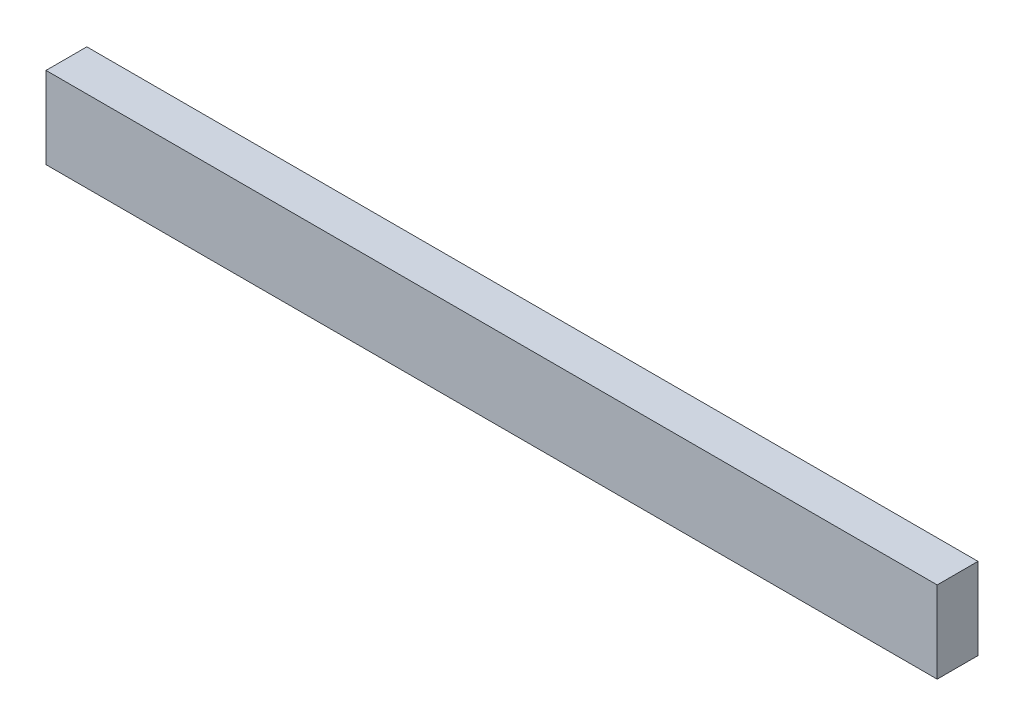
SolidWorks part; units mm, degrees
material "Sapin"
ref_plane "Plan de face" through (0, 0, 0) normal (0, 0, 1) x (1, 0, 0)
ref_plane "Plan de dessus" through (0, 0, 0) normal (0, 1, 0) x (1, 0, 0)
ref_plane "Plan de droite" through (0, 0, 0) normal (1, 0, 0) x (0, 0, -1)
sketch "Esquisse1" plane through (0, 0, 0) normal (0, 0, 1) x (1, 0, 0)
  line L1 (-262, -24) -> (262, -24)
  line L2 (-262, -24) -> (-262, 24)
  line L3 (-262, 24) -> (262, 24)
  line L4 (262, -24) -> (262, 24)
  line L5 (-262, -24) -> (262, 24) construction
  line L6 (-262, 24) -> (262, -24) construction
  point P0 (0, 0)
  dimension "D1" = 48
  dimension "D2" = 524
extrude "Boss.-Extru.1" add sketch "Esquisse1" along normal mid plane 24
sketch "Esquisse2" plane through (0, 0, -12) normal (0, 0, -1) x (-1, 0, 0)
  line L0 (-250, 15) -> (-250, -15) construction
  line L1 (-262, 0) -> (-250, 0) construction
  line L2 (-262, -24) -> (-262, 24) construction
  line L3 (0, 0) -> (0, -24) construction
  line L4 (262, -24) -> (-262, -24) construction
  line L5 (262, 0) -> (250, 0) construction
  line L6 (250, 15) -> (250, -15) construction
  circle A0 centre (-250, 15) radius 2.5
  circle A1 centre (-250, -15) radius 2.5
  circle A2 centre (250, -15) radius 2.5
  circle A3 centre (250, 15) radius 2.5
  dimension "D1" = 5
  dimension "D2" = 12
  dimension "D3" = 30
extrude "Enlèv. mat.-Extru.1" [suppressed] cut sketch "Esquisse2" against normal through all
